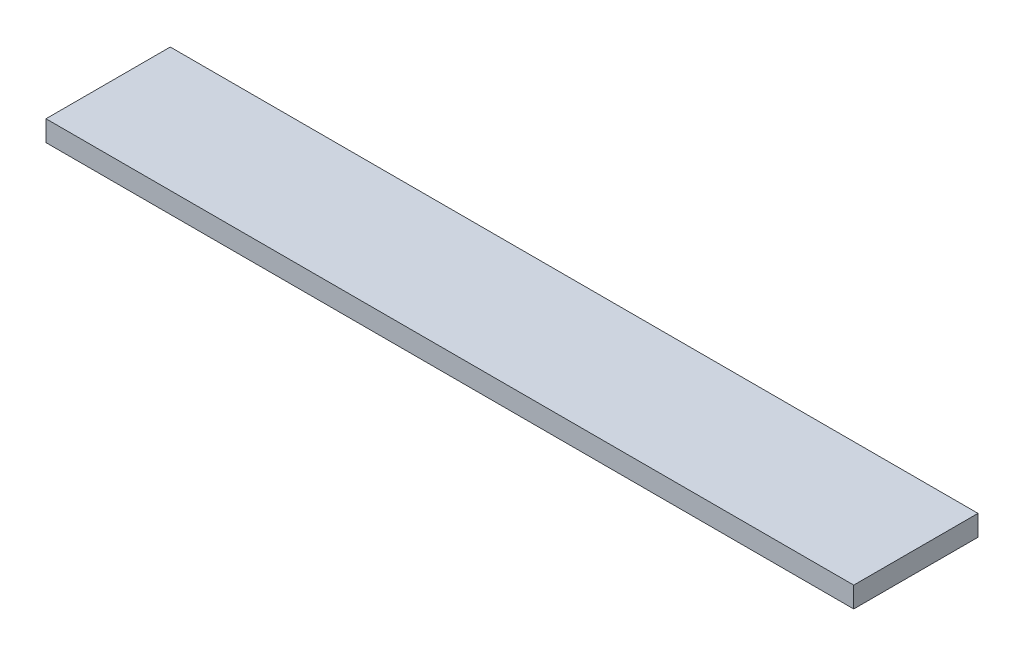
SolidWorks part; units mm, degrees
ref_plane "Front Plane" through (0, 0, 0) normal (0, 0, 1) x (1, 0, 0)
ref_plane "Top Plane" through (0, 0, 0) normal (0, 1, 0) x (1, 0, 0)
ref_plane "Right Plane" through (0, 0, 0) normal (1, 0, 0) x (0, 0, -1)
sketch "Sketch1" plane through (0, 0, 0) normal (0, 1, 0) x (1, 0, 0)
  line L1 (-49.53, 11.8496) -> (49.53, 11.8496)
  line L2 (-49.53, 11.8496) -> (-49.53, -3.3904)
  line L3 (-49.53, -3.3904) -> (49.53, -3.3904)
  line L4 (49.53, 11.8496) -> (49.53, -3.3904)
  dimension "D1" = 49.53
  dimension "D2" = 99.06
  dimension "D3" = 15.24
extrude "Boss-Extrude1" add sketch "Sketch1" along normal blind 2.54
